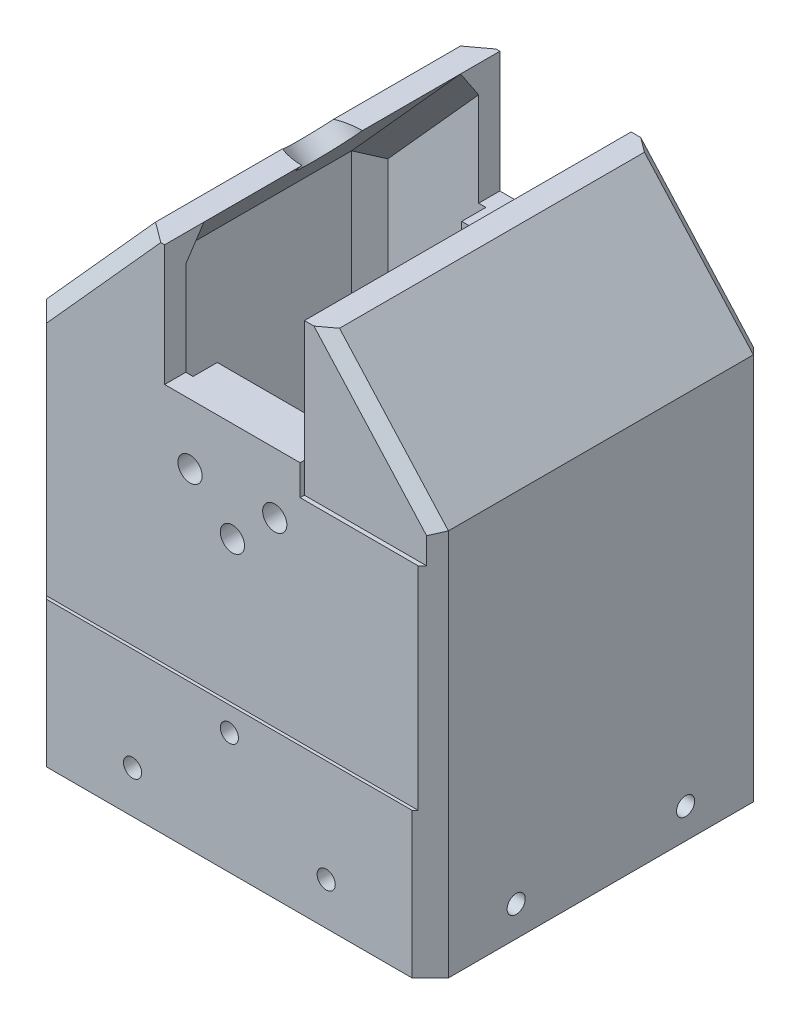
SolidWorks part; units mm, degrees
ref_plane "前视基准面" through (0, 0, 0) normal (0, 0, 1) x (1, 0, 0)
ref_plane "上视基准面" through (0, 0, 0) normal (0, 1, 0) x (1, 0, 0)
ref_plane "右视基准面" through (0, 0, 0) normal (1, 0, 0) x (0, 0, -1)
sketch "草图1" plane through (0, 0, 0) normal (0, 1, 0) x (1, 0, 0)
  line L0 (33.2, 28.2) -> (-33.2, 28.2)
  line L1 (-33.2, 28.2) -> (-33.2, -28.2)
  line L2 (-33.2, -28.2) -> (33.2, -28.2)
  line L3 (33.2, -28.2) -> (33.2, 28.2)
  line L4 (29.2, 24.2) -> (10, 24.2)
  line L5 (10, 24.2) -> (10, 20.2)
  line L6 (10, 20.2) -> (-10, 20.2)
  line L7 (-10, 20.2) -> (-10, 24.2)
  line L8 (-10, 24.2) -> (-29.2, 24.2)
  line L9 (-29.2, 24.2) -> (-29.2, -24.2)
  line L10 (-29.2, -24.2) -> (-10, -24.2)
  line L11 (-10, -24.2) -> (-10, -20.2)
  line L12 (-10, -20.2) -> (10, -20.2)
  line L13 (10, -20.2) -> (10, -24.2)
  line L14 (10, -24.2) -> (29.2, -24.2)
  line L15 (29.2, -24.2) -> (29.2, 24.2)
  dimension "D1" = 66.4
  dimension "D2" = 56.4
  dimension "D3" = 4
  dimension "D4" = 4
  dimension "D5" = 4
  dimension "D6" = 20
  dimension "D7" = 4
  dimension "D8" = 4
  dimension "D9" = 4
  dimension "D10" = 19.2
  dimension "D11" = 19.2
  dimension "D12" = 20
  dimension "D13" = 4
  dimension "D14" = 20.2
  dimension "D15" = 20.2
  dimension "D16" = 29.2
extrude "凸台-拉伸1" add sketch "草图1" along normal blind 64
sketch "草图3" plane through (0, 0, 28.2) normal (0, 0, 1) x (1, 0, 0)
  line L0 (-33.2, 64) -> (-11.2, 64)
  line L1 (-33.2, 64) -> (33.2, 64) construction
  line L2 (-11.2, 64) -> (-11.2, 84)
  line L3 (-11.2, 84) -> (-15.2, 84)
  line L4 (-15.2, 84) -> (-33.2, 64)
  line L5 (33.2, 64) -> (11.2, 64)
  line L6 (11.2, 64) -> (11.2, 84)
  line L7 (11.2, 84) -> (15.2, 84)
  line L8 (15.2, 84) -> (33.2, 64)
  dimension "D1" = 22
  dimension "D2" = 20
  dimension "D3" = 4
  dimension "D4" = 22
  dimension "D5" = 4
  dimension "D6" = 20
extrude "凸台-拉伸2" add sketch "草图3" against normal blind 4
sketch "草图4" plane through (0, 0, -28.2) normal (0, 0, -1) x (-1, 0, 0)
  line L0 (-33.2, 64) -> (-11.2, 64)
  line L1 (-33.2, 64) -> (33.2, 64) construction
  line L2 (-11.2, 64) -> (-11.2, 84)
  line L3 (-11.2, 84) -> (-15.2, 84)
  line L4 (-15.2, 84) -> (-33.2, 64)
  line L6 (33.2, 64) -> (11.2, 64)
  line L7 (11.2, 64) -> (11.2, 84)
  line L8 (11.2, 84) -> (15.2, 84)
  line L9 (15.2, 84) -> (33.2, 64)
  dimension "D1" = 22
  dimension "D2" = 20
  dimension "D3" = 4
  dimension "D4" = 22
  dimension "D5" = 20
  dimension "D6" = 4
extrude "凸台-拉伸3" add sketch "草图4" against normal blind 4
sketch "草图5" plane through (0, 0, -24.2) normal (0, 0, 1) x (1, 0, 0)
  line L0 (-29.2, 64) -> (-33.2, 64)
  line L1 (-33.2, 64) -> (-15.2, 84)
  line L2 (-15.2, 84) -> (-11.2, 84)
  line L3 (-11.2, 84) -> (-29.2, 64)
  line L7 (11.2, 84) -> (29.2, 64)
  line L8 (29.2, 64) -> (33.2, 64)
  line L9 (33.2, 64) -> (15.2, 84)
  line L10 (15.2, 84) -> (11.2, 84)
extrude "凸台-拉伸4" add sketch "草图5" along normal up to next
sketch "草图8" plane through (0, 0, 0) normal (1, 0, 0) x (0, 0, -1)
  line L0 (-20.2, 45) -> (-24.2, 45)
  line L1 (-20.2, 64) -> (-20.2, 0) construction
  line L2 (-24.2, 64) -> (-24.2, 0) construction
  line L3 (-24.2, 45) -> (-24.2, 0)
  line L4 (-24.2, 0) -> (-20.2, 0)
  line L5 (-20.2, 0) -> (-20.2, 45)
  line L6 (-28.2, 64) -> (28.2, 64) construction
  line L7 (20.2, 45) -> (24.2, 45)
  line L8 (20.2, 64) -> (20.2, 0) construction
  line L9 (24.2, 64) -> (24.2, 0) construction
  line L10 (24.2, 45) -> (24.2, 0)
  line L11 (-28.2, 0) -> (28.2, 0) construction
  line L12 (24.2, 0) -> (20.2, 0)
  line L13 (20.2, 0) -> (20.2, 45)
  line L14 (20.2, 64) -> (24.2, 64) construction
  dimension "D1" = 19
  dimension "D2" = 19
extrude "切除-拉伸5" cut sketch "草图8" against normal mid plane 20
sketch "草图7" plane through (0, 0, 20.2) normal (0, 0, -1) x (-1, 0, 0)
  line L0 (10, 45) -> (-10, 45) construction
  line L1 (10, 64) -> (10, 45) construction
  line L2 (-10, 64) -> (-10, 45) construction
  circle A0 centre (0, 47.5) radius 0.75
  circle A1 centre (-7, 54) radius 0.75
  circle A2 centre (7, 54) radius 0.75
  dimension "D4" = 9
  dimension "D6" = 1.5
  dimension "D7" = 1.5
  dimension "D8" = 1.5
  dimension "D1" = 2.5
  dimension "D2" = 3
  dimension "D3" = 3
  dimension "D5" = 9
  dimension "D9" = 10
sketch "草图9" plane through (-33.2, 0, 0) normal (-1, 0, 0) x (0, 0, 1)
  line L1 (-28.2, 0) -> (28.2, 0) construction
  circle A0 centre (14, 5) radius 1.5
  circle A1 centre (-14, 5) radius 1.5
  dimension "D5" = 3
  dimension "D6" = 3
  dimension "D1" = 14
  dimension "D2" = 14
  dimension "D3" = 5
  dimension "D4" = 5
extrude "切除-拉伸6" cut sketch "草图9" against normal through all
sketch "草图11" plane through (0, 0, 28.2) normal (0, 0, 1) x (1, 0, 0)
  line L1 (-33.2, 0) -> (33.2, 0) construction
  circle A0 centre (0, 20) radius 1.5
  circle A1 centre (-16, 7) radius 1.5
  circle A2 centre (16, 7) radius 1.5
  dimension "D3" = 3
  dimension "D4" = 3
  dimension "D5" = 3
  dimension "D1" = 16
  dimension "D2" = 16
  dimension "D6" = 7
  dimension "D7" = 7
  dimension "D8" = 20
extrude "切除-拉伸8" cut sketch "草图11" against normal through all
chamfer "倒角1" distance 3 angle 45 16 edges at (-20.2, 74, -24.2) (-29.2, 32, -24.2) (20.2, 74, 24.2) (29.2, 32, 24.2) (20.2, 74, -24.2) (29.2, 32, -24.2) (-24.2, 74, 28.2) (-24.2, 74, -28.2) (-33.2, 32, 28.2) (-33.2, 32, -28.2) (24.2, 74, 28.2) (24.2, 74, -28.2) (33.2, 32, -28.2) (33.2, 32, 28.2)
extrude "切除-拉伸9" cut sketch "草图7" against normal up to next
sketch "草图12" plane through (0, 0, 28.2) normal (0, 0, 1) x (1, 0, 0)
  circle A0 centre (-7, 54) radius 2
  circle A1 centre (7, 54) radius 2
  circle A2 centre (0, 47.5) radius 2
  dimension "D1" = 4
  dimension "D2" = 4
  dimension "D3" = 4
extrude "切除-拉伸10" cut sketch "草图12" against normal blind 5
sketch "草图13" plane through (0, 0, -28.2) normal (0, 0, -1) x (-1, 0, 0)
  line L0 (-10, 64) -> (-10, 45) construction
  line L1 (10, 64) -> (10, 45) construction
  line L2 (10, 45) -> (-10, 45) construction
  circle A0 centre (-7.6, 47.4) radius 0.75
  circle A1 centre (-7.6, 60.8) radius 0.75
  circle A2 centre (7.6, 60.8) radius 0.75
  circle A3 centre (7.6, 47.4) radius 0.75
  dimension "D1" = 1.5
  dimension "D2" = 1.5
  dimension "D3" = 1.5
  dimension "D4" = 1.5
  dimension "D6" = 2.4
  dimension "D8" = 13.4
  dimension "D9" = 2.4
  dimension "D10" = 2.4
  dimension "D11" = 2.4
  dimension "D12" = 2.4
  dimension "D5" = 2.4
  dimension "D7" = 13.4
extrude "切除-拉伸11" cut sketch "草图13" against normal up to next
sketch "草图14" plane through (0, 0, -28.2) normal (0, 0, -1) x (-1, 0, 0)
  circle A0 centre (-7.6, 60.8) radius 2
  circle A1 centre (7.6, 60.8) radius 2
  circle A2 centre (-7.6, 47.4) radius 2
  circle A3 centre (7.6, 47.4) radius 2
  dimension "D1" = 4
  dimension "D2" = 4
  dimension "D3" = 4
  dimension "D4" = 4
extrude "切除-拉伸12" cut sketch "草图14" against normal blind 5
sketch "草图16" plane through (33.2, 0, 0) normal (1, 0, 0) x (0, 0, -1)
  line L0 (-28.2, 24) -> (-27.7, 24)
  line L1 (-28.2, 0) -> (-28.2, 62.8488) construction
  line L2 (-27.7, 24) -> (-27.7, 84)
  line L3 (-28.1732, 84) -> (-25.2, 84) construction
  line L4 (-27.7, 84) -> (-28.2, 84)
  line L5 (-25.2, 64) -> (25.2, 64) construction
  line L7 (-28.2, 84) -> (-28.2, 24)
  line L8 (28.2, 24) -> (28.2, 84)
  line L9 (28.2, 62.8488) -> (28.2, 0) construction
  line L10 (28.2, 84) -> (27.7, 84)
  line L11 (25.2, 84) -> (28.1732, 84) construction
  line L12 (27.7, 84) -> (27.7, 24)
  line L13 (27.7, 24) -> (28.2, 24)
  line L15 (24.2, 64) -> (28.2, 64) construction
  dimension "D1" = 0.5
  dimension "D2" = 0.5
  dimension "D3" = 40
  dimension "D5" = 40
extrude "切除-拉伸16" cut sketch "草图16" against normal through all
sketch "草图17" plane through (33.2, 0, 0) normal (1, 0, 0) x (0, 0, -1)
  line L0 (-27.7, 59) -> (-27, 59)
  line L1 (-27.7, 24) -> (-27.7, 63.0407) construction
  line L2 (-27, 59) -> (-27, 84)
  line L3 (-27.7, 84) -> (-25.2, 84) construction
  line L4 (-27, 84) -> (-27.7, 84)
  line L5 (-27.7, 84) -> (-27.7, 59)
  line L6 (27.7, 59) -> (27, 59)
  line L8 (27.7, 63.0407) -> (27.7, 24) construction
  line L9 (27, 59) -> (27, 84)
  line L10 (25.2, 84) -> (27.7, 84) construction
  line L11 (27, 84) -> (27.7, 84)
  line L12 (27.7, 84) -> (27.7, 59)
  dimension "D1" = 0.7
  dimension "D2" = 0.7
  dimension "D3" = 25
  dimension "D4" = 25
extrude "切除-拉伸17" cut sketch "草图17" against normal blind 22
sketch "草图18" plane through (-50.1657, 45.1492, 0) normal (-0.7433, 0.669, 0) x (0, 0, 1)
  line L0 (21.2, 54.9443) -> (-21.2, 54.9443) construction
  line L1 (-5, 54.9443) -> (5, 54.9443)
  arc A0 (-5, 54.9443) -> (5, 54.9443) centre (0, 54.9443) ccw
  dimension "D1" = 5
extrude "切除-拉伸18" cut sketch "草图18" against normal blind 10
equation "\"0。9\"=0.831065"
